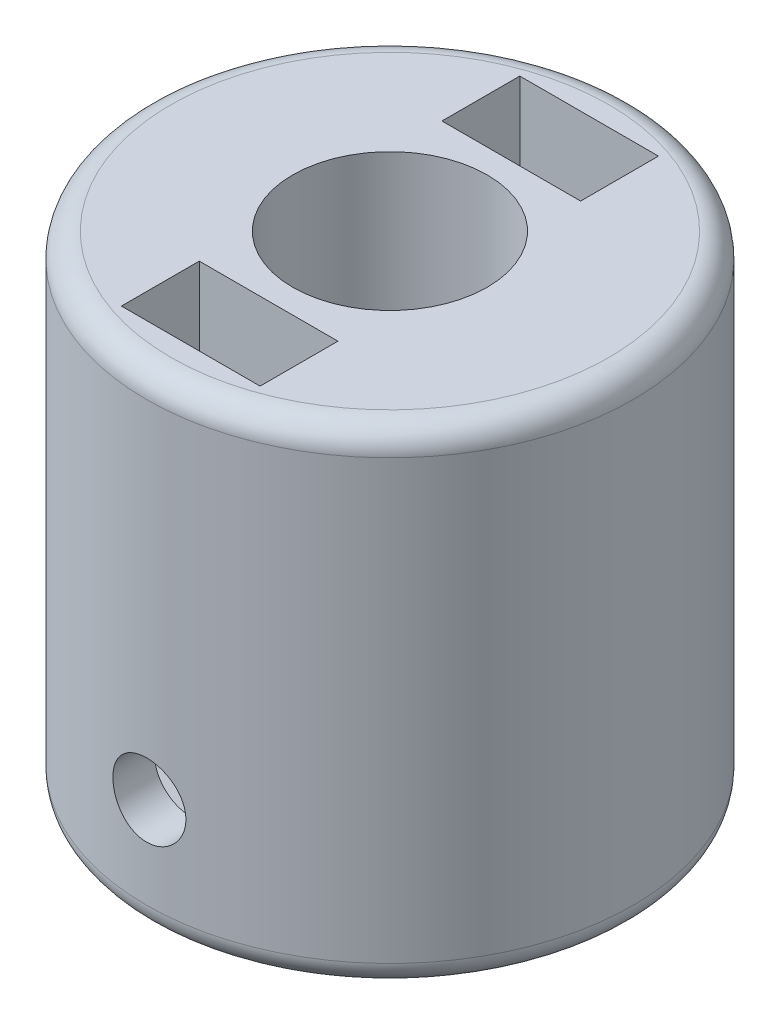
SolidWorks part; units mm, degrees
ref_plane "Front Plane" through (0, 0, 0) normal (0, 0, 1) x (1, 0, 0)
ref_plane "Top Plane" through (0, 0, 0) normal (0, 1, 0) x (1, 0, 0)
ref_plane "Right Plane" through (0, 0, 0) normal (1, 0, 0) x (0, 0, -1)
sketch "Sketch1" plane through (0, 0, 0) normal (0, 1, 0) x (1, 0, 0)
  circle A0 centre (0, 0) radius 3.175
  circle A1 centre (0, 0) radius 10
  dimension "D1" = 6.35
  dimension "D2" = 20
extrude "Boss-Extrude1" add sketch "Sketch1" along normal blind 20
sketch "Sketch2" plane through (0, 20, 0) normal (0, 1, 0) x (1, 0, 0)
  line L2 (-2.85, -4.9875) -> (2.85, -4.9875)
  line L3 (-2.85, -4.9875) -> (-2.85, -8.1875)
  line L4 (-2.85, -8.1875) -> (2.85, -8.1875)
  line L5 (2.85, -4.9875) -> (2.85, -8.1875)
  line L6 (-2.85, -4.9875) -> (2.85, -8.1875) construction
  line L7 (-2.85, -8.1875) -> (2.85, -4.9875) construction
  point P7 (0, -6.5875)
  dimension "D1" = 5.7
  dimension "D2" = 3.2
extrude "Cut-Extrude1" cut sketch "Sketch2" against normal blind 17
sketch "Sketch3" plane through (0, 0, 4.9875) normal (0, 0, 1) x (1, 0, 0)
  line L0 (-2.85, 3) -> (0, 1.4513)
  line L1 (0, 1.4513) -> (2.85, 3)
  line L2 (2.85, 3) -> (-2.85, 3)
extrude "Cut-Extrude2" cut sketch "Sketch3" along normal blind 3.3
sketch "Sketch4" plane through (0, 20, 0) normal (0, 1, 0) x (1, 0, 0)
  circle A0 centre (0, 0) radius 4
  dimension "D1" = 8
extrude "Cut-Extrude3" cut sketch "Sketch4" against normal blind 9.3
sketch "Sketch5" plane through (0, 20, 0) normal (0, 1, 0) x (1, 0, 0)
  line L5 (2.85, 4.9875) -> (2.85, 8.1875)
  line L6 (-2.85, 8.1875) -> (2.85, 8.1875)
  line L7 (-2.85, 4.9875) -> (-2.85, 8.1875)
  line L8 (-2.85, 4.9875) -> (2.85, 4.9875)
extrude "Cut-Extrude5" cut sketch "Sketch5" against normal blind 7.8
sketch "Sketch6" plane through (0, 0, -4.9875) normal (0, 0, -1) x (-1, 0, 0)
  line L0 (-2.85, 12.2) -> (0, 10.7)
  line L1 (3.175, 10.7) -> (-3.175, 10.7) construction
  line L2 (0, 10.7) -> (2.85, 12.2)
  line L3 (2.85, 12.2) -> (-2.85, 12.2)
extrude "Cut-Extrude6" cut sketch "Sketch6" along normal blind 3.2
fillet "Fillet1" radius 1 2 edges at (0, 0, 10) (0, 20, 10)
sketch "Sketch7" plane through (0, 0, -4.9875) normal (0, 0, -1) x (-1, 0, 0)
  circle A1 centre (0, 13.8368) radius 1.5
extrude "Cut-Extrude7" cut sketch "Sketch7" along normal blind 10.2
sketch "Sketch8" plane through (0, 0, 4.9875) normal (0, 0, 1) x (1, 0, 0)
  circle A5 centre (0, 4.7483) radius 1.5
extrude "Cut-Extrude8" cut sketch "Sketch8" along normal blind 7.2
